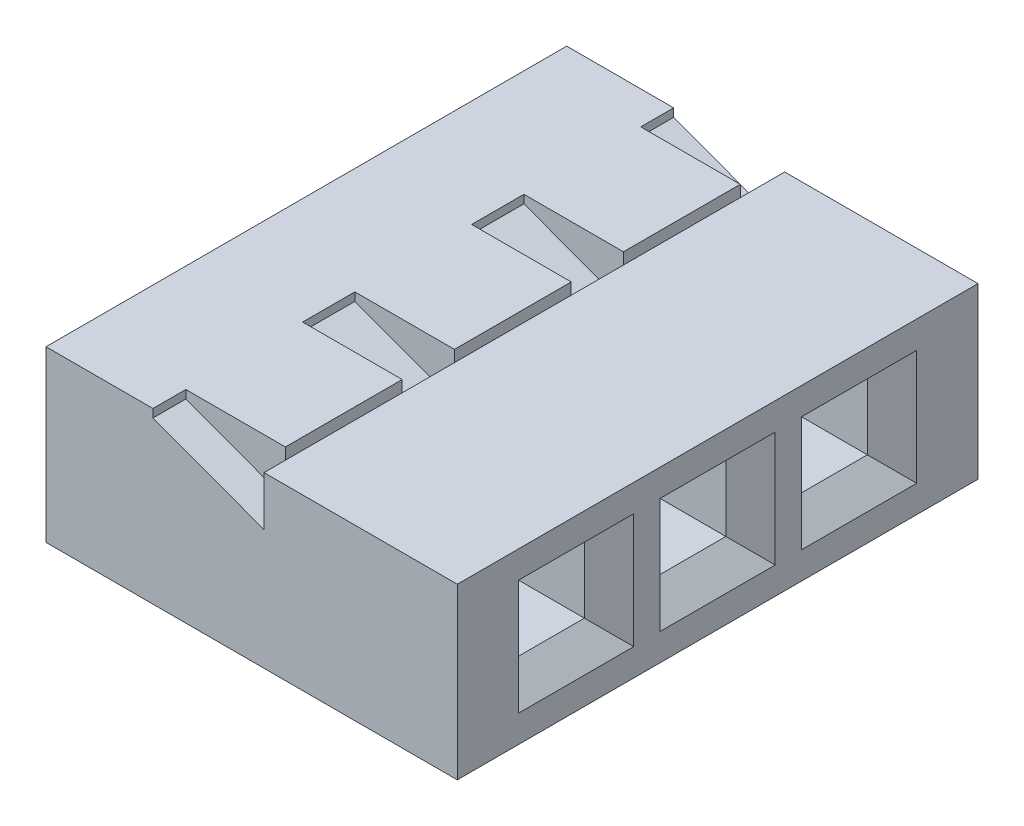
SolidWorks part; units mm, degrees
ref_plane "Front Plane" through (0, 0, 0) normal (0, 0, 1) x (1, 0, 0)
ref_plane "Top Plane" through (0, 0, 0) normal (0, 1, 0) x (1, 0, 0)
ref_plane "Right Plane" through (0, 0, 0) normal (1, 0, 0) x (0, 0, -1)
sketch "Sketch1" plane through (0, 0, 0) normal (1, 0, 0) x (0, 0, -1)
  line L0 (0, 5.639) -> (0, -4.1212) construction
  line L1 (-3.165, 1.03) -> (3.165, 1.03)
  line L2 (-3.165, 1.03) -> (-3.165, -1.03)
  line L3 (-3.165, -1.03) -> (3.165, -1.03)
  line L4 (3.165, 1.03) -> (3.165, -1.03)
  line L5 (-3.165, 1.03) -> (3.165, -1.03) construction
  line L6 (-3.165, -1.03) -> (3.165, 1.03) construction
  line L7 (-6.6526, 0) -> (5.231, 0) construction
  line L9 (-0.4, 0.4) -> (0.4, 0.4)
  line L10 (-0.4, 0.4) -> (-0.4, -0.4)
  line L11 (-0.4, -0.4) -> (0.4, -0.4)
  line L12 (0.4, 0.4) -> (0.4, -0.4)
  line L13 (-0.4, 0.4) -> (0.4, -0.4) construction
  line L14 (-0.4, -0.4) -> (0.4, 0.4) construction
  line L15 (-2.12, 0.4) -> (-1.32, 0.4)
  line L16 (-2.12, 0.4) -> (-2.12, -0.4)
  line L17 (-2.12, -0.4) -> (-1.32, -0.4)
  line L18 (-1.32, 0.4) -> (-1.32, -0.4)
  line L19 (-2.12, 0.4) -> (-1.32, -0.4) construction
  line L20 (-2.12, -0.4) -> (-1.32, 0.4) construction
  line L21 (1.32, 0.4) -> (2.12, 0.4)
  line L22 (1.32, 0.4) -> (1.32, -0.4)
  line L23 (1.32, -0.4) -> (2.12, -0.4)
  line L24 (2.12, 0.4) -> (2.12, -0.4)
  line L25 (1.32, 0.4) -> (2.12, -0.4) construction
  line L26 (1.32, -0.4) -> (2.12, 0.4) construction
  point P0 (0, 0)
  point P10 (0, 0)
  point P15 (-1.72, 0)
  point P20 (1.72, 0)
  dimension "D1" = 6.33
  dimension "D2" = 2.06
  dimension "D3" = 0.8
  dimension "D4" = 0.8
  dimension "D5" = 1.045
  dimension "D6" = 1.045
extrude "Boss-Extrude1" add sketch "Sketch1" along normal mid plane 5
sketch "Sketch2" plane through (0, 0, 3.165) normal (0, 0, 1) x (1, 0, 0)
  line L0 (-2.5, 1.03) -> (-2.5, -1.03) construction
  line L1 (-1.2, 2.7222) -> (0.15, 2.7222)
  line L2 (-1.2, 2.7222) -> (-1.2, 0.93)
  line L3 (2.5, 1.03) -> (-2.5, 1.03) construction
  line L4 (0.15, 2.7222) -> (0.15, 0.43)
  line L5 (-1.2, 2.7222) -> (0.15, 0.43) construction
  line L6 (-1.2, 0.93) -> (0.15, 2.7222) construction
  line L8 (0.15, 0.43) -> (-1.2, 0.93)
  point P0 (-0.6076, 1.7164)
  dimension "D1" = 1.3
  dimension "D2" = 1.35
  dimension "D3" = 0.6
  dimension "D4" = 0.1
extrude "Cut-Extrude1" cut sketch "Sketch2" against normal blind 7.25
sketch "Sketch3" plane through (-1.2, 0, 0) normal (1, 0, 0) x (0, 0, -1)
  line L1 (-1.72, 1.03) -> (-1.72, -0.4) construction
  line L2 (0, 1.03) -> (0, -0.4) construction
  line L3 (1.72, 1.03) -> (1.72, -0.4) construction
  line L4 (-2.12, -0.4) -> (-1.32, -0.4) construction
  line L5 (-0.4, -0.4) -> (0.4, -0.4) construction
  line L6 (1.32, -0.4) -> (2.12, -0.4) construction
  line L9 (3.165, 1.03) -> (-3.165, 1.03) construction
  line L10 (-2.765, 1.03) -> (-1.345, 1.03)
  line L11 (-2.765, 1.03) -> (-2.765, 0.4)
  line L12 (-2.765, 0.4) -> (-1.345, 0.4)
  line L13 (-1.345, 1.03) -> (-1.345, 0.4)
  line L15 (-0.71, 1.03) -> (0.71, 1.03)
  line L16 (-0.71, 1.03) -> (-0.71, 0.4)
  line L17 (-0.71, 0.4) -> (0.71, 0.4)
  line L18 (0.71, 1.03) -> (0.71, 0.4)
  line L19 (1.345, 1.03) -> (2.765, 1.03)
  line L20 (1.345, 1.03) -> (1.345, 0.4)
  line L21 (1.345, 0.4) -> (2.765, 0.4)
  line L22 (2.765, 1.03) -> (2.765, 0.4)
  line L24 (-1.32, 0.4) -> (-2.12, 0.4) construction
  line L25 (-3.165, 1.03) -> (-3.165, -1.03) construction
  line L26 (3.165, -1.03) -> (3.165, 1.03) construction
  dimension "D1" = 1.42
  dimension "D2" = 0.4
  dimension "D5" = 0.4
extrude "Boss-Extrude2" add sketch "Sketch3" along normal blind 1.21
chamfer "Chamfer1" distance 0.3 angle 45 24 edges at (2.5, 0, 1.32) (2.5, -0.4, 1.72) (2.5, 0, 2.12) (2.5, 0.4, 1.72) (2.5, -0.4, -1.72) (2.5, 0, -2.12) (2.5, 0.4, -1.72) (2.5, 0, -1.32) (2.5, -0.4, 0) (2.5, 0, -0.4) (2.5, 0.4, 0) (2.5, 0, 0.4) (-2.5, -0.4, 0) (-2.5, -0.4, 1.72) (-2.5, 0, 2.12) (-2.5, 0.4, 1.72) (-2.5, 0.4, 0) (-2.5, 0.4, -1.72) (-2.5, 0, -2.12) (-2.5, -0.4, -1.72) (-2.5, 0, 1.32) (-2.5, 0, 0.4) (-2.5, 0, -0.4) (-2.5, 0, -1.32)
